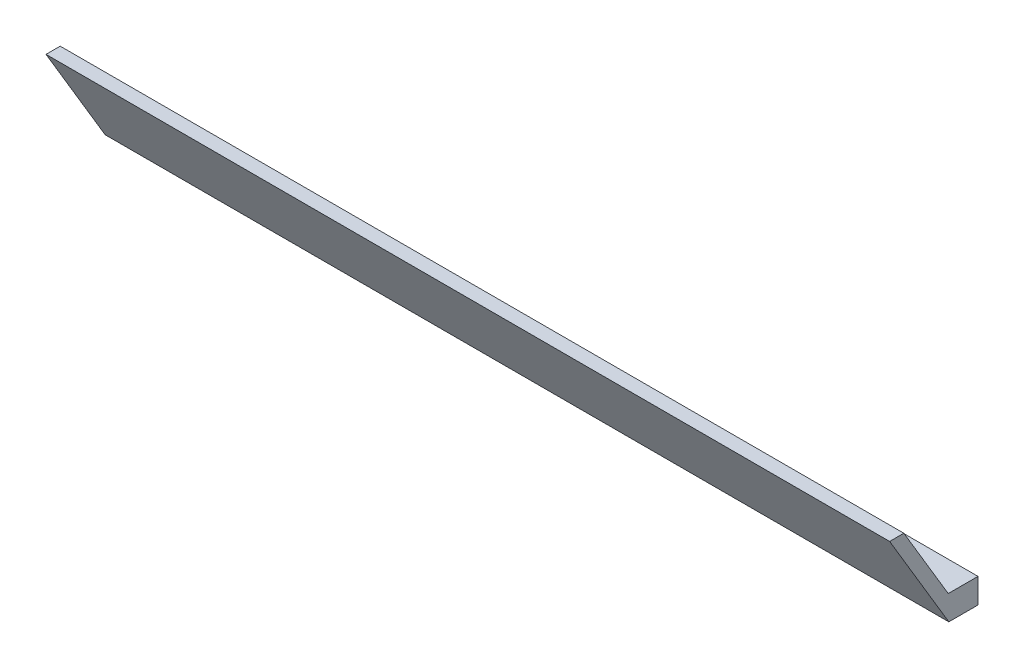
SolidWorks part; units mm, degrees
ref_plane "前视基准面" through (0, 0, 0) normal (0, 0, 1) x (1, 0, 0)
ref_plane "上视基准面" through (0, 0, 0) normal (0, 1, 0) x (1, 0, 0)
ref_plane "右视基准面" through (0, 0, 0) normal (1, 0, 0) x (0, 0, -1)
other "Configuration Table"
sketch "草图1" plane through (0, 0, 0) normal (1, 0, 0) x (0, 0, -1)
  line L0 (0, 0) -> (6, 0)
  line L1 (6, 0) -> (6, -5)
  line L2 (6, -5) -> (0.1202, -5)
  line L3 (0.1202, -5) -> (-11.8053, 15)
  line L4 (-11.8053, 15) -> (-8.9441, 15)
  line L5 (-8.9441, 15) -> (0, 0)
  dimension "D1" = 5
  dimension "D3" = 6
  dimension "D4" = 20
extrude "凸台-拉伸1" add sketch "草图1" along normal mid plane 170
